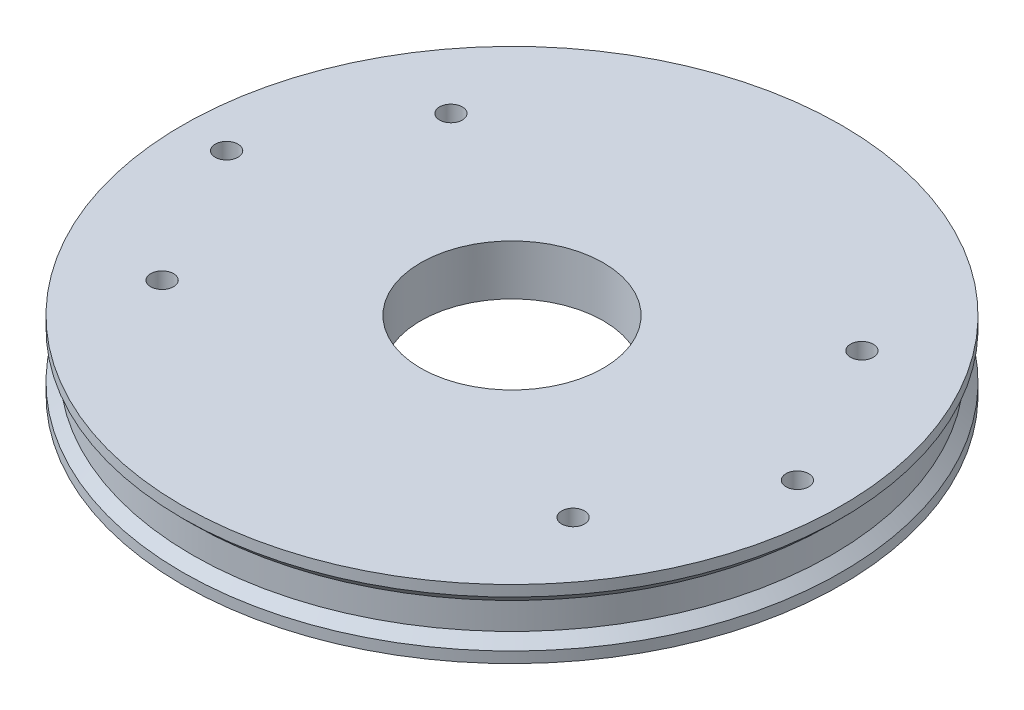
SolidWorks part; units mm, degrees
ref_plane "Front Plane" through (0, 0, 0) normal (0, 0, 1) x (1, 0, 0)
ref_plane "Top Plane" through (0, 0, 0) normal (0, 1, 0) x (1, 0, 0)
ref_plane "Right Plane" through (0, 0, 0) normal (1, 0, 0) x (0, 0, -1)
sketch "Sketch1" plane through (0, 0, 0) normal (0, 1, 0) x (1, 0, 0)
  circle A0 centre (0, 0) radius 72.175
  circle A1 centre (0, 0) radius 20
  dimension "D1" = 144.35
  dimension "D2" = 40
extrude "Boss-Extrude1" add sketch "Sketch1" along normal mid plane 15
ref_axis "Axis1" through (0, 6.6, 0) along (0, -1, 0)
sketch "Sketch2" plane through (0, 0, 0) normal (0, 0, 1) x (1, 0, 0)
  line L0 (72.175, -5.115) -> (72.175, 5.115)
  line L1 (72.175, -7.5) -> (72.175, 7.5) construction
  line L2 (72.175, 5.115) -> (70, 2.94)
  line L3 (70, 2.94) -> (70, -2.94)
  line L4 (70, 0) -> (72.175, 0) construction
  line L5 (72.175, -5.115) -> (70, -2.94)
  dimension "D1" = 5.115
  dimension "D2" = 2.175
  dimension "D3" = 45
revolve "Cut-Revolve1" cut sketch "Sketch2" angle 360 about axis through (0, 6.6, 0) along (0, -1, 0)
sketch "Sketch3" plane through (0, -7.5, 0) normal (0, -1, 0) x (1, 0, 0)
  circle A0 centre (0, 0) radius 30.5
  dimension "D1" = 61
extrude "Cut-Extrude1" cut sketch "Sketch3" against normal blind 4
sketch "Sketch4" plane through (0, 7.5, 0) normal (0, 1, 0) x (1, 0, 0)
  line L0 (0, 0) -> (62.5, 0) construction
  line L1 (45, -31.6228) -> (45, 31.6228) construction
  circle A0 centre (62.5, 0) radius 2.5
  circle A1 centre (0, 0) radius 55 construction
  circle A2 centre (45, 31.6228) radius 2.5
  circle A3 centre (45, -31.6228) radius 2.5
  dimension "D2" = 5
  dimension "D3" = 110
  dimension "D5" = 5
  dimension "D6" = 5
  dimension "D1" = 62.5
  dimension "D4" = 45
extrude "Cut-Extrude2" cut sketch "Sketch4" against normal through all
mirror "Mirror1" about plane through (0, 0, 0) normal (1, 0, 0) of "Cut-Extrude2"
